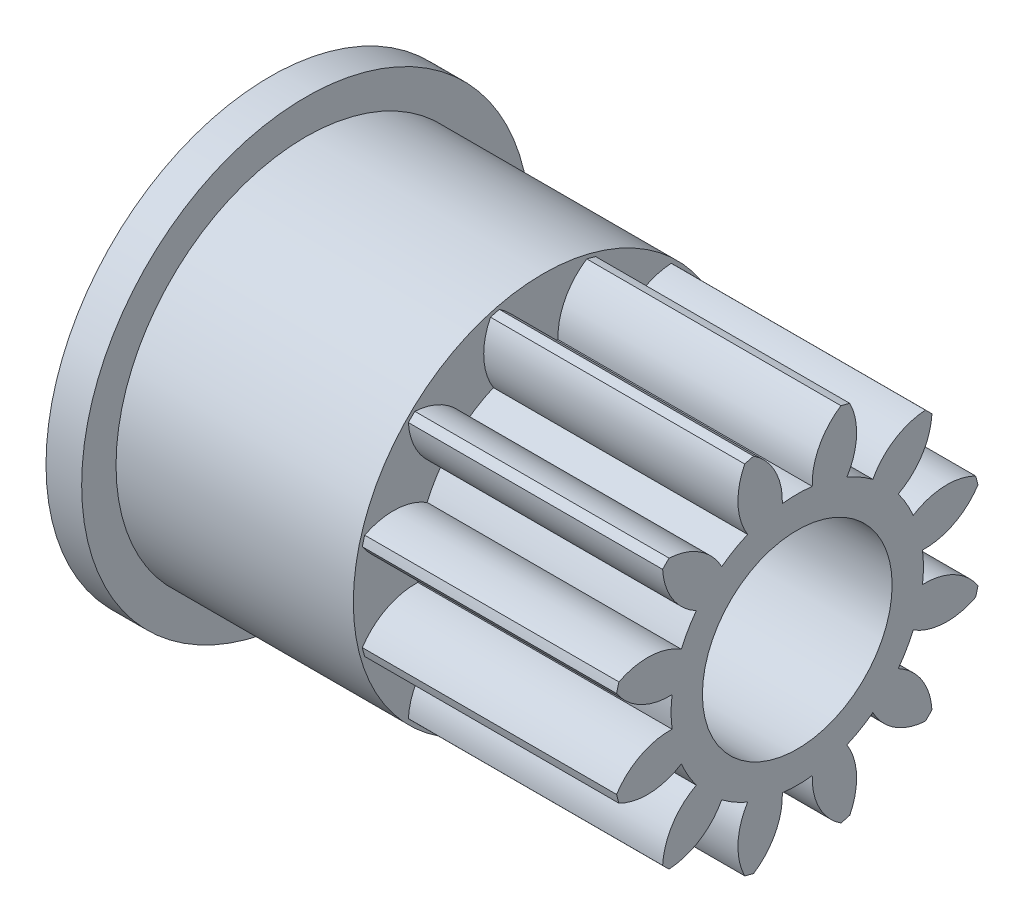
SolidWorks part; units mm, degrees
ref_plane "Plane1" through (0, 0, 0) normal (0, 0, 1) x (1, 0, 0)
ref_plane "Plane2" through (0, 0, 0) normal (0, 1, 0) x (1, 0, 0)
ref_plane "Plane3" through (0, 0, 0) normal (1, 0, 0) x (0, 0, -1)
sketch "HoldingSke" plane through (0, 0, 0) normal (0, 1, 0) x (1, 0, 0)
  line L0 (0, 0) -> (1.3974, -0.297)
  line L1 (-15, 0) -> (100, 0) construction
  line L2 (0, 0) -> (-2.1039, 2.3779)
  line L3 (0, 0) -> (-11.863, 4.5341)
  line L4 (0, 0) -> (8.4473, 1.7955)
  line L5 (0, 0) -> (-46.8476, -17.4728)
  line L6 (0, 0) -> (-5.5541, -3.7473)
  line L7 (-2.1039, 2.3779) -> (8.6586, 51.2059)
  line L8 (-76.2, 54.61) -> (-76.1, 54.61)
  line L9 (-71.009, 38.7566) -> (-53.1078, 45.2721)
  line L10 (-76.2, 71.12) -> (104.1128, 71.12)
  line L11 (0, 0) -> (-6.7, 0)
  line L12 (-76.2, 101.6) -> (-76.173, 101.6)
  line L13 (24.9733, 27.94) -> (52.9518, 28.4284)
  line L14 (24.9733, 27.94) -> (24.9743, 27.94)
  line L15 (24.9733, 27.94) -> (100.4006, 29.5858)
  line L16 (-63.627, -0.7) -> (-12.827, -0.7)
  circle A0 centre (0, 0) radius 0.4
  circle A1 centre (0, 0) radius 3.324
  circle A2 centre (0, 0) radius 37.5
  circle A3 centre (0, 0) radius 0.4
  dimension "MHD" = 6.648
  dimension "Hub_dia" = 75
  dimension "Bore" = 0.8
  dimension "MBD" = 0.8
  dimension "Num_teeth" = 12
  dimension "Pitch_radius" = 180.3128
  dimension "Pitch" = 1.4286
  dimension "Width" = 6.7
  dimension "Overall_len" = 50
  dimension "Show_teeth" = 12
  dimension "Thickness" = 6.7
  dimension "OAL" = 50.0001
  dimension "T_dim" = 0.1
  dimension "Ap" = 20
  dimension "H" = 19.05
  dimension "Backlash" = 0.027
  dimension "Addendum_fac" = 1
  dimension "Dedendum_fac" = 1.25
  dimension "Clearance_fac" = 0.25
  dimension "Dedendum_add" = 0.001
  dimension "Module" = 0.7
sketch "BasProSke" plane through (0, 0, 0) normal (0, 1, 0) x (1, 0, 0)
  line L0 (-10, 0) -> (60, 0) construction
  line L1 (0, 0) -> (0, 4.9)
  line L2 (0, 0) -> (6.7, 0)
  line L3 (6.7, 0) -> (6.7, 4.9)
  line L4 (6.7, 4.9) -> (0, 4.9)
  dimension "Diameter" = 9.8
  dimension "Thickness" = 6.7
revolve "Base-Revolve" add sketch "BasProSke" angle 360 about L0
sketch "TooCutSke" plane through (0, 0, 0) normal (1, 0, 0) x (0, 0, -1)
  line L1 (0, 0) -> (0, 107) construction
  line L2 (0, 0) -> (-0.5954, 4.1576) construction
  line L3 (0, 0) -> (-2.1586, 8.0559) construction
  line L4 (-0.5954, 4.1576) -> (-1.0793, 4.0279) construction
  arc A0 (0.3941, 3.3006) -> (-0.3941, 3.3006) centre (0, 0) ccw
  arc A1 (1.1807, 4.7818) -> (-1.1807, 4.7818) centre (0, 0) ccw
  circle A2 centre (0, 0) radius 4.2 construction
  circle A3 centre (0, 0) radius 3.9467 construction
  arc A4 (-0.3941, 3.3006) -> (-1.1807, 4.7818) centre (-2.0731, 3.3584) ccw
  arc A5 (1.1807, 4.7818) -> (0.3941, 3.3006) centre (2.0731, 3.3584) ccw
  dimension "Root_dia" = 6.648
  dimension "Overcut_dia" = 9.8508
  dimension "Pitch_dia" = 8.4
  dimension "Base_dia" = 7.8934
  dimension "Flank_rad" = 1.68
  dimension "Half_ang" = 15
  dimension "Half_CT" = 0.501
extrude "ToothCut" cut sketch "TooCutSke" along normal through all
fillet "Breaks" [suppressed] radius 0.014
fillet "RootFillets" [suppressed] radius 0.176
pattern_circular "TeethCuts" count 12 every 30 about axis through (-10, 0, 0) along (1, 0, 0) of "ToothCut", "RootFillets", "Breaks"
sketch "HubNeaOneSke" plane through (0, 0, 0) normal (-1, 0, 0) x (0, 0, 1)
  circle A0 centre (0, 0) radius 3.324
  dimension "Diameter" = 6.648
extrude "HubNearOne" [suppressed] add sketch "HubNeaOneSke" along normal blind 43.3001
sketch "HubNeaBotSke" plane through (0, 0, 0) normal (-1, 0, 0) x (0, 0, 1)
  circle A0 centre (0, 0) radius 3.324
  dimension "Diameter" = 6.648
extrude "HubNearBoth" [suppressed] add sketch "HubNeaBotSke" along normal blind 21.65
ref_plane "FarPln" through (6.7, 0, 0) normal (1, 0, 0) x (0, 0, -1)
sketch "HubFarSke" plane through (6.7, 0, 0) normal (1, 0, 0) x (0, 0, -1)
  circle A0 centre (0, 0) radius 3.324
  dimension "Diameter" = 6.648
extrude "HubFar" [suppressed] add sketch "HubFarSke" along normal blind 21.65
sketch "BorSke" plane through (0, 0, 0) normal (1, 0, 0) x (0, 0, -1)
  circle A0 centre (0, 0) radius 0.4
  dimension "Diameter" = 0.8
extrude "Bore" cut sketch "BorSke" along normal mid plane 100.0001
sketch "KeySke" plane through (0, 0, 0) normal (1, 0, 0) x (0, 0, -1)
  line L0 (-0.05, 0) -> (-0.05, 0.5)
  line L1 (-0.05, 0.5) -> (0.05, 0.5)
  line L2 (0.05, 0.5) -> (0.05, 0)
  line L3 (0, 0) -> (0, 34) construction
  line L4 (-0.05, 0) -> (0.05, 0)
  dimension "Offset" = 0.5
  dimension "Width" = 0.1
extrude "Keyway" [suppressed] cut sketch "KeySke" along normal mid plane 100.0001
pattern_circular "Keyway2" [suppressed] count 2 every 90 about axis through (-10, 0, 0) along (1, 0, 0)
sketch "Sketch1" plane through (0, 0, 0) normal (-1, 0, 0) x (0, 0, 1)
  circle A0 centre (0, 0) radius 5
  dimension "D1" = 10
extrude "Boss-Extrude1" add sketch "Sketch1" along normal offset from surface (7.1938 mm away) 13.8938 up to face at (6.7, 0, 0)
sketch "Sketch3" plane through (-7.1938, 0, 0) normal (-1, 0, 0) x (0, 0, 1)
  circle A0 centre (0, 0) radius 5.9055
  dimension "D1" = 11.811
extrude "Boss-Extrude2" add sketch "Sketch3" against normal blind 0.9398
sketch "Sketch2" plane through (-7.1938, 0, 0) normal (-1, 0, 0) x (0, 0, 1)
  circle A0 centre (0, 0) radius 2.5
  dimension "D1" = 5
extrude "Cut-Extrude1" cut sketch "Sketch2" against normal through all
equation "' \"Module@HoldingSke\" = 6.35"
equation "' \"Num_teeth@HoldingSke\" = 12"
equation "' \"Ap@HoldingSke\" =  20"
equation "' \"Width@HoldingSke\" = 0.5 * 25.4"
equation "' \"Hub_dia@HoldingSke\"= 1 * 25.4"
equation "' \"Overall_len@HoldingSke\" = 1.0 * 25.4"
equation "' \"Bore@HoldingSke\" = 0.75 * 25.4"
equation "' \"T_dim@HoldingSke\" = 0.1 * 25.4"
equation "' \"Width@KeySke\" = 0.25 * 25.4"
equation "' \"Show_teeth@HoldingSke\" = 13"
equation "' \"Backlash@HoldingSke\" = 0.009 * 25.4"
equation "' \"Addendum_fac@HoldingSke\" = 1.0"
equation "' \"Dedendum_fac@HoldingSke\" = 1.25"
equation "' \"Dedendum_add@HoldingSke\" = 0.00005 * 25.4"
equation "' \"Clearance_fac@HoldingSke\" = 0.25"
equation "\"Pitch@HoldingSke\" = 1 / \"Module@HoldingSke\""
equation "\"Overcut_dia@TooCutSke\" = (\"Num_teeth@HoldingSke\" + 2 * \"Addendum_fac@HoldingSke\") / \"Pitch@HoldingSke\" + 0.002 * 25.4"
equation "\"Pitch_dia@TooCutSke\" = \"Num_teeth@HoldingSke\" / \"Pitch@HoldingSke\""
equation "\"Base_dia@TooCutSke\" = \"Num_teeth@HoldingSke\" / \"Pitch@HoldingSke\" * cos((\"Ap@HoldingSke\"  * 3.14159265 / 180))"
equation "\"Root_dia@TooCutSke\" = (\"Num_teeth@HoldingSke\" + 2) / \"Pitch@HoldingSke\" - 2 * (\"Addendum_fac@HoldingSke\" + \"Dedendum_fac@HoldingSke\") / \"Pitch@HoldingSke\" - \"Dedendum_add@HoldingSke\" * 2"
equation "\"Half_ang@TooCutSke\" = 180 / \"Num_teeth@HoldingSke\""
equation "\"Half_CT@TooCutSke\" = \"Num_teeth@HoldingSke\" / \"Pitch@HoldingSke\" * sin((3.14159265 / 2 / \"Num_teeth@HoldingSke\")) / 2 - 7 * \"Backlash@HoldingSke\" / 4"
equation "\"Flank_rad@TooCutSke\" = \"Num_teeth@HoldingSke\" / \"Pitch@HoldingSke\" / 5"
equation "\"Radius@RootFillets\" = \"Clearance_fac@HoldingSke\" / \"Pitch@HoldingSke\" + \"Dedendum_add@HoldingSke\""
equation "\"Break_rad@Breaks\" = 0.02 / \"Pitch@HoldingSke\""
equation "\"Thickness@HoldingSke\" = \"Width@HoldingSke\""
equation "\"OAL@HoldingSke\" = \"Thickness@HoldingSke\""
equation "\"MHD@HoldingSke\" = (\"Num_teeth@HoldingSke\" + 2) / \"Pitch@HoldingSke\" - 2 * (\"Addendum_fac@HoldingSke\" + \"Dedendum_fac@HoldingSke\")  / \"Pitch@HoldingSke\" - \"Dedendum_add@HoldingSke\" * 2"
equation "\"MBD@HoldingSke\" = (\"Num_teeth@HoldingSke\" + 2) / \"Pitch@HoldingSke\" - 2 * (\"Addendum_fac@HoldingSke\" + \"Dedendum_fac@HoldingSke\")  / \"Pitch@HoldingSke\" - \"Dedendum_add@HoldingSke\" * 2 - 0.002 * 25.4"
equation "\"MHD@HoldingSke\" = ((sgn( \"MHD@HoldingSke\" - \"Hub_dia@HoldingSke\" )-1)*( \"MHD@HoldingSke\" - \"Hub_dia@HoldingSke\" ))/-2+ \"Hub_dia@HoldingSke\""
equation "\"MBD@HoldingSke\" = ((sgn( \"MBD@HoldingSke\" - \"Bore@HoldingSke\" )-1)*( \"MBD@HoldingSke\" - \"Bore@HoldingSke\" ))/-2+ \"Bore@HoldingSke\""
equation "\"OAL@HoldingSke\" = ((sgn( \"OAL@HoldingSke\" - \"Overall_len@HoldingSke\" )+1)*( \"OAL@HoldingSke\" - \"Overall_len@HoldingSke\" ))/2 + \"Overall_len@HoldingSke\" + 0.000002 * 25.4"
equation "\"Num_teeth@TeethCuts\" = int( \"Show_teeth@HoldingSke\" ) + 1"
equation "\"Num_teeth@TeethCuts\" = ((sgn( \"Num_teeth@TeethCuts\" - \"Num_teeth@HoldingSke\" )-1)*( \"Num_teeth@TeethCuts\" - \"Num_teeth@HoldingSke\" ))/-2+ \"Num_teeth@HoldingSke\""
equation "\"Num_teeth@TeethCuts\" = ((sgn( \"Num_teeth@TeethCuts\" - 2.0)+1)*( \"Num_teeth@TeethCuts\" - 2.0))/2 +2.0"
equation "\"Angle@TeethCuts\" = 360.0 / \"Num_teeth@HoldingSke\""
equation "\"Diameter@BasProSke\" = (\"Num_teeth@HoldingSke\" + 2 * \"Addendum_fac@HoldingSke\") / \"Pitch@HoldingSke\""
equation "\"Thickness@BasProSke\"  = \"Thickness@HoldingSke\""
equation "' \"Fillet_rad@BasProSke\" =  \"Thickness@HoldingSke\" * 0.05"
equation "\"MHD@HoldingSke\" = ((sgn( \"MHD@HoldingSke\" - \"Root_dia@TooCutSke\" )-1)*( \"MHD@HoldingSke\" - \"Root_dia@TooCutSke\" ))/-2+ \"Root_dia@TooCutSke\""
equation "\"Diameter@HubNeaOneSke\" = \"MHD@HoldingSke\""
equation "\"Length@HubNearOne\" = \"OAL@HoldingSke\" - \"Thickness@BasProSke\""
equation "\"Diameter@HubNeaBotSke\" = \"MHD@HoldingSke\""
equation "\"Length@HubNearBoth\" = ( \"OAL@HoldingSke\" - \"Thickness@BasProSke\" ) / 2.0"
equation "\"Thickness@FarPln\" = \"Thickness@BasProSke\""
equation "\"Diameter@HubFarSke\" = \"MHD@HoldingSke\""
equation "\"Length@HubFar\" = ( \"OAL@HoldingSke\" - \"Thickness@BasProSke\" ) / 2.0"
equation "\"Diameter@BorSke\" = \"MBD@HoldingSke\""
equation "\"D1@Bore\" = \"OAL@HoldingSke\" * 2.0"
equation "\"D1@Keyway\" = \"OAL@HoldingSke\" * 2.0"
equation "\"Offset@KeySke\" = \"T_dim@HoldingSke\" + \"MBD@HoldingSke\" / 2.0"
